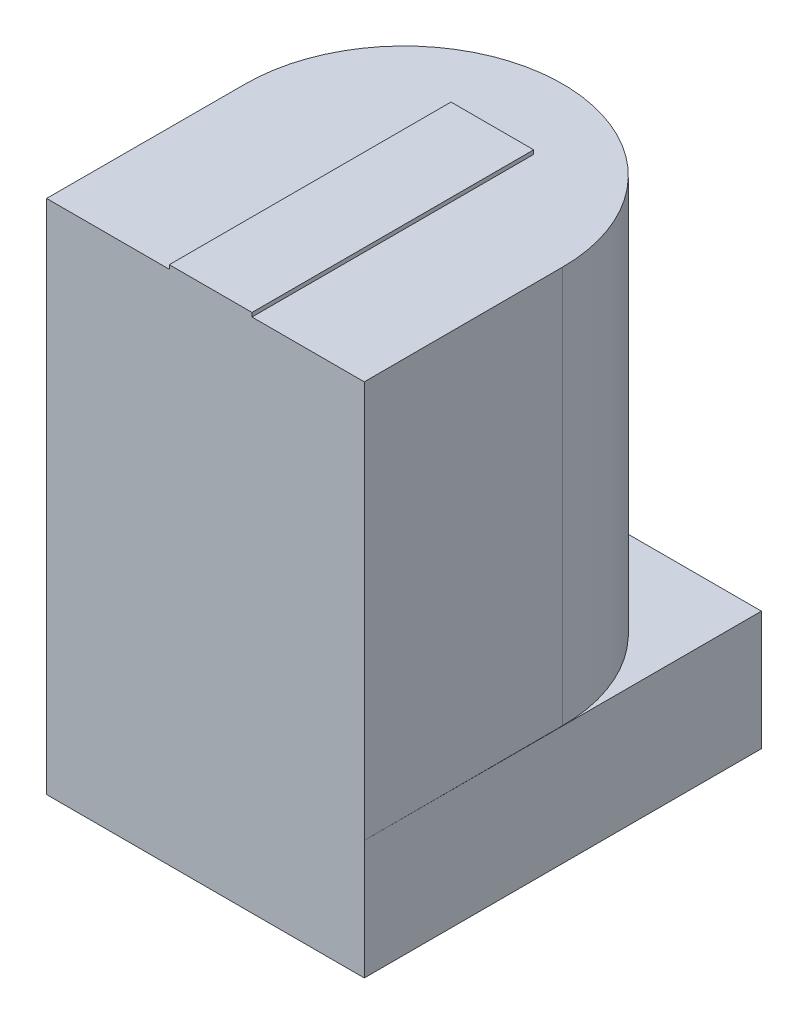
SolidWorks part; units mm, degrees
ref_plane "前视基准面" through (0, 0, 0) normal (0, 0, 1) x (1, 0, 0)
ref_plane "上视基准面" through (0, 0, 0) normal (0, 1, 0) x (1, 0, 0)
ref_plane "右视基准面" through (0, 0, 0) normal (1, 0, 0) x (0, 0, -1)
sketch "草图1" plane through (0, 0, 0) normal (0, 1, 0) x (1, 0, 0)
  line L1 (0, 0) -> (8, 0)
  line L2 (0, 0) -> (0, 10)
  line L3 (0, 10) -> (8, 10)
  line L4 (8, 0) -> (8, 10)
  dimension "D1" = 8
  dimension "D2" = 10
extrude "凸台-拉伸1" add sketch "草图1" along normal blind 3
sketch "草图2" plane through (0, 3, 0) normal (0, 1, 0) x (1, 0, 0)
  line L0 (4, 11.8576) -> (4, -2.7603) construction
  line L1 (-2.115, 5) -> (11.7166, 5) construction
  line L2 (0.006, 5) -> (0, 0)
  line L3 (0, 0) -> (8, 0)
  line L4 (8, 0) -> (7.994, 5)
  arc A0 (7.994, 5) -> (0.006, 5) centre (4, 5) ccw
extrude "凸台-拉伸2" add sketch "草图2" along normal blind 10
sketch "草图3" plane through (0, 0, 0) normal (0, -1, 0) x (1, 0, 0)
  line L0 (4, -12.0873) -> (4, 3.5306) construction
  circle A0 centre (4, -5.5123) radius 2.5
extrude "切除-拉伸1" cut sketch "草图3" against normal blind 10
sketch "草图4" plane through (0, 13, 0) normal (0, 1, 0) x (1, 0, 0)
  line L0 (0, 0) -> (8, 0) construction
  line L1 (3.09, 7.0929) -> (5.1729, 7.0929)
  line L2 (3.09, 7.0929) -> (3.09, 0)
  line L3 (3.09, 0) -> (5.1729, 0)
  line L4 (5.1729, 7.0929) -> (5.1729, 0)
extrude "凸台-拉伸3" add sketch "草图4" along normal blind 0.1
